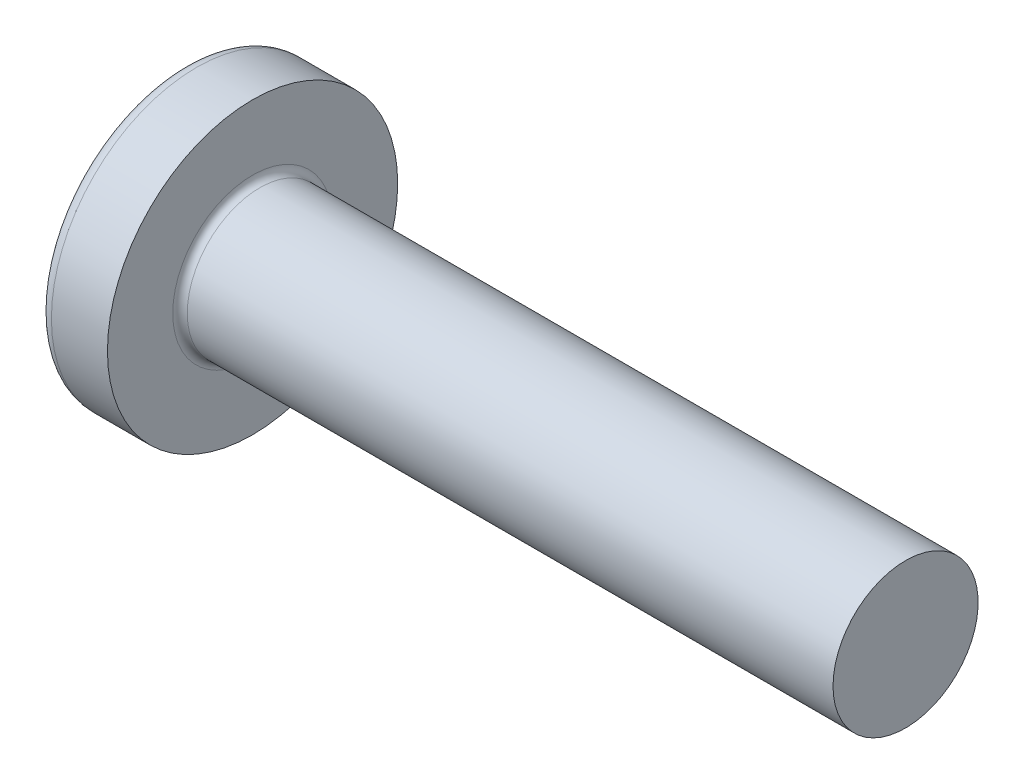
SolidWorks part; units mm, degrees
material "普通碳钢"
ref_plane "Plane1" through (0, 0, 0) normal (0, 0, 1) x (1, 0, 0)
ref_plane "Plane2" through (0, 0, 0) normal (0, 1, 0) x (1, 0, 0)
ref_plane "Plane3" through (0, 0, 0) normal (1, 0, 0) x (0, 0, -1)
sketch "BodySke" plane through (0, 0, 0) normal (0, 0, 1) x (1, 0, 0)
  line L0 (3.1, 2) -> (3.1, 4)
  line L1 (3.45, 6.35) -> (3.45, -3.175) construction
  line L2 (-25.4, 0) -> (127, 0) construction
  line L3 (21.1, 0) -> (0, 0)
  line L4 (3.1, 2) -> (21.1, 2)
  line L5 (21.1, 2) -> (21.1, 0)
  line L6 (1.5553, 4) -> (3.1, 4)
  line L8 (15.1, 6.35) -> (15.1, -3.175) construction
  arc A0 (1.2654, 3.8534) -> (0, 0) centre (6.5, 0) ccw
  arc A2 (1.2654, 3.8534) -> (1.5553, 4) centre (1.5553, 3.64) cw
  dimension "Head_crown_rad" = 6.5
  dimension "Head_fillet_rad" = 0.36
  dimension "Length" = 18
  dimension "Head_ht" = 3.1
  dimension "Head_dia" = 8
  dimension "Advance" = 0.7
  dimension "Thread_nom" = 6
  dimension "Diameter" = 4
revolve "Base-Revolve" add sketch "BodySke"
cosmetic thread "ThreadCosmetic" [suppressed]
fillet "Fillet1" radius 0.2 1 edges at (3.1, 0, 2)
sketch "Sketch3" plane through (0, 0, 0) normal (1, 0, 0) x (0, 0, -1)
  line L0 (0.515, -2.15) -> (-0.515, -2.15)
  line L1 (0.515, -2.15) -> (0.515, 2.15)
  line L2 (-0.515, 2.15) -> (0.515, 2.15)
  line L3 (-0.515, 2.15) -> (-0.515, -2.15)
  dimension "Cross_dia" = 4.3
  dimension "D1" = 2.15
  dimension "Cross_width" = 1.03
  dimension "D2" = 0.515
ref_plane "Plane4" through (2.34, 0, 0) normal (1, 0, 0) x (0, 0, -1)
sketch "Sketch4" plane through (2.34, 0, 0) normal (1, 0, 0) x (0, 0, -1)
  line L0 (0.515, -0.9833) -> (-0.515, -0.9833)
  line L1 (0.515, -0.9833) -> (0.515, 0.9833)
  line L2 (-0.515, 0.9833) -> (0.515, 0.9833)
  line L3 (-0.515, 0.9833) -> (-0.515, -0.9833)
  dimension "D1" = 1.03
  dimension "D2" = 1.9666
  dimension "D3" = 0.515
  dimension "D4" = 0.9833
loft "Recess" cut profiles "Sketch3", "Sketch4"
pattern_circular "RecPat" count 2 every 90 about axis through (0, 0, 0) along (1, 0, 0) of "Recess"
sketch "RecCorSke" plane through (0, 0, 0) normal (0, 0, 1) x (1, 0, 0)
  line L0 (-3.175, 0) -> (15.875, 0) construction
  line L1 (-25.4, 0) -> (127, 0) construction
  line L2 (0, 0) -> (0, 1.0146)
  line L3 (0, 1.0146) -> (2.34, 0.851)
  line L4 (2.34, 0.851) -> (2.6165, 0)
  line L5 (2.6165, 0) -> (0, 0)
  dimension "Diameter" = 1.702
  dimension "Depth" = 2.34
  dimension "Draft_angle" = 4
  dimension "Bottom_angle" = 18
revolve "RecessCore" cut sketch "RecCorSke" angle 360 about L0
sketch "ThdSchSke" plane through (0, 0, 0) normal (0, 0, 1) x (1, 0, 0)
  line L0 (9.1, -1.61) -> (8.8269, -2)
  line L1 (9.1, -1.61) -> (9.3731, -2)
  line L2 (9.3731, -2) -> (9.3731, -2.5)
  line L3 (-3.175, 0) -> (5.1513, 0) construction
  line L5 (9.3731, -2.5) -> (8.8269, -2.5)
  line L6 (8.8269, -2.5) -> (8.8269, -2)
  dimension "Diameter" = 4
  dimension "SideAngle" = 55
  dimension "VeeAngle" = 70
  dimension "Thread_minor" = 3.22
  dimension "Overcut" = 5
  dimension "Start" = 9.1
revolve "ThreadSchematic" [suppressed] cut sketch "ThdSchSke" angle 360 about L3
pattern_linear "ThdSchPat" [suppressed]
sketch "草图1" plane through (21.1, 0, 0) normal (1, 0, 0) x (0, 0, -1)
  circle A0 centre (0, 0) radius 2 construction
  circle A1 centre (0, 0) radius 2
equation "\"D1@Sketch3\" = \"Cross_dia@Sketch3\" / 2"
equation "\"D2@Sketch3\" = \"Cross_width@Sketch3\" / 2"
equation "\"Depth@RecCorSke\" = \"Cross_depth@Plane4\""
equation "\"D1@Sketch4\" = \"Cross_width@Sketch3\""
equation "\"D2@Sketch4\" = \"Cross_dia@Sketch3\" - 2.0 * \"Cross_depth@Plane4\" * tan(26.5  * 0.017453292)"
equation "\"D3@Sketch4\" = \"D1@Sketch4\" / 2"
equation "\"D4@Sketch4\" = \"D2@Sketch4\" / 2"
equation "\"Thread_length@ThreadCosmetic\" = ((sgn( (\"Length@BodySke\" - \"Advance@BodySke\" * 2.0 ) - \"Thread_nom@BodySke\" )-1)*( (\"Length@BodySke\" - \"Advance@BodySke\" * 2.0 ) - \"Thread_nom@BodySke\" ))/-2+ \"Thread_nom@BodySke\""
equation "\"Thread_minor@ThdSchSke\" = \"Thread_minor@ThreadCosmetic\""
equation "\"Diameter@ThdSchSke\" = \"Diameter@BodySke\""
equation "\"Overcut@ThdSchSke\" = \"Diameter@BodySke\" * 1.25"
equation "\"Start@ThdSchSke\" = \"Head_ht@BodySke\" + \"Length@BodySke\" - \"Thread_length@ThreadCosmetic\"  '---Non-countersunk---"
equation "\"Num_threads@ThdSchPat\" = int( \"Thread_length@ThreadCosmetic\" / \"Advance@BodySke\" + 0.999 )  + 1"
equation "\"Advance@ThdSchPat\" = \"Thread_length@ThreadCosmetic\" /  (\"Num_threads@ThdSchPat\" - 1) 'relax it"
